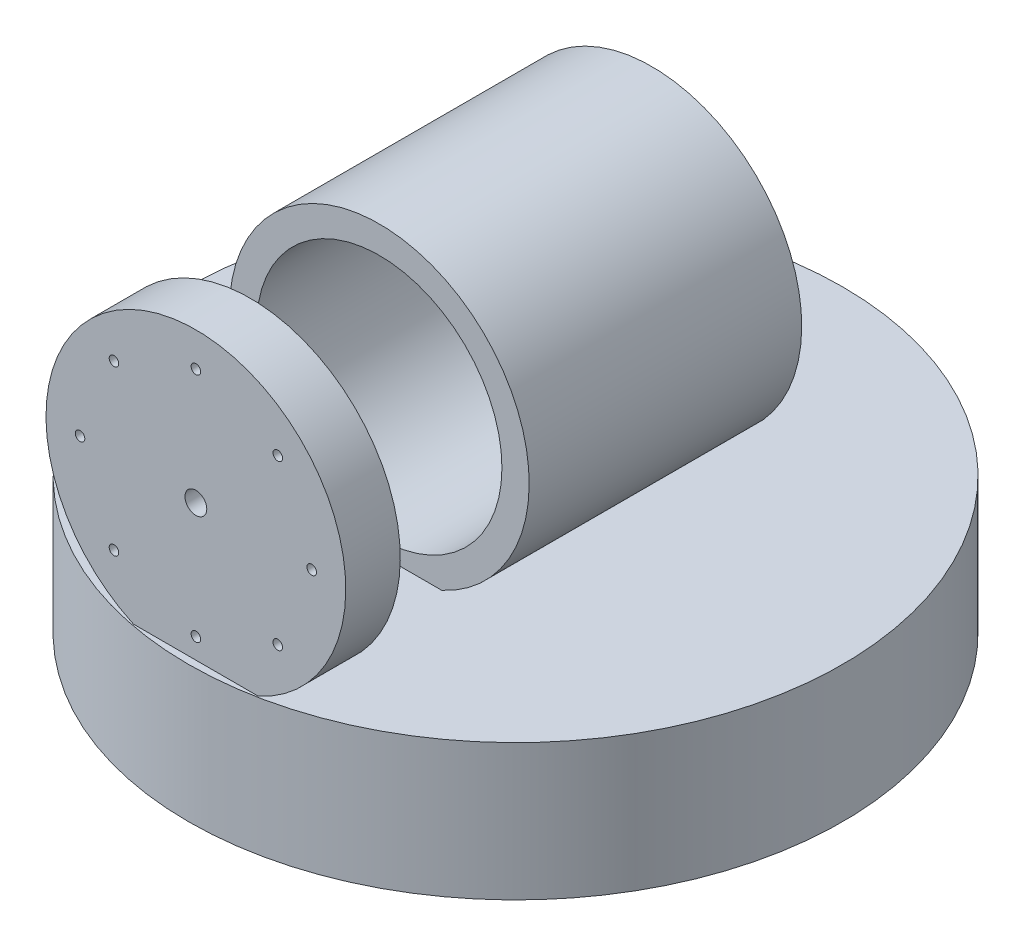
SolidWorks part; units mm, degrees
ref_plane "前视基准面" through (0, 0, 0) normal (0, 0, 1) x (1, 0, 0)
ref_plane "上视基准面" through (0, 0, 0) normal (0, 1, 0) x (1, 0, 0)
ref_plane "右视基准面" through (0, 0, 0) normal (1, 0, 0) x (0, 0, -1)
other "Configuration Table"
sketch "草图1" plane through (0, 0, 0) normal (0, 1, 0) x (1, 0, 0)
  circle A0 centre (0, 0) radius 120
extrude "凸台-拉伸1" add sketch "草图1" along normal blind 50
sketch "草图2" plane through (0, 0, 0) normal (0, 0, 1) x (1, 0, 0)
  line L0 (0, 50) -> (0, 100) construction
  line L1 (120, 50) -> (-120, 50) construction
  circle A0 centre (0, 100) radius 50
extrude "拉伸-薄壁1" add sketch "草图2" along normal blind 50 and the other way blind 50 thin thin type mid plane wall 10
sketch "草图3" plane through (0, 0, 50) normal (0, 0, 1) x (1, 0, 0)
  line L1 (-60, 152.3851) -> (120, 152.3851)
  line L2 (-60, 152.3851) -> (-60, 50)
  line L3 (-60, 50) -> (120, 50)
  line L4 (120, 152.3851) -> (120, 50)
  line L5 (-60, 152.3851) -> (120, 50) construction
  line L6 (-60, 50) -> (120, 152.3851) construction
  point P0 (30, 101.1925)
ref_plane "基准面1" through (0, 0, 55) normal (0, 0, 1) x (1, 0, 0)
sketch "草图4" plane through (0, 0, 55) normal (0, 0, 1) x (1, 0, 0)
  line L1 (-60, 152.3851) -> (120, 152.3851)
  line L2 (-60, 152.3851) -> (-60, 50)
  line L3 (-60, 50) -> (120, 50)
  line L4 (120, 152.3851) -> (120, 50)
  line L5 (-60, 152.3851) -> (120, 50) construction
  line L6 (-60, 50) -> (120, 152.3851) construction
  point P0 (30, 101.1925)
sketch "草图7" plane through (0, 0, 0) normal (0, -1, 0) x (1, 0, 0)
  circle A1 centre (17.25, 0) radius 2
  circle A2 centre (8.625, -14.9389) radius 2
  circle A3 centre (-8.625, -14.9389) radius 2
  circle A4 centre (-17.25, 0) radius 2
  circle A5 centre (-8.625, 14.9389) radius 2
  circle A6 centre (8.625, 14.9389) radius 2
  point P17 (0, 0)
  dimension "D2" = 4
  dimension "D3" = 6
extrude "切除-拉伸2" cut sketch "草图7" against normal blind 3
ref_plane "基准面2" through (0, 0, 97.3) normal (0, 0, 1) x (1, 0, 0)
sketch "草图8" plane through (0, 0, 97.3) normal (0, 0, 1) x (1, 0, 0)
  circle A0 centre (0, 100) radius 55
extrude "凸台-拉伸2" add sketch "草图8" along normal blind 20
sketch "草图9" plane through (0, 0, 97.3) normal (0, 0, -1) x (-1, 0, 0)
  circle A1 centre (42.5, 100) radius 1.75
  circle A2 centre (30.052, 69.948) radius 1.75
  circle A3 centre (0, 57.5) radius 1.75
  circle A4 centre (-30.052, 69.948) radius 1.75
  circle A5 centre (-42.5, 100) radius 1.75
  circle A6 centre (-30.052, 130.052) radius 1.75
  circle A7 centre (0, 142.5) radius 1.75
  circle A8 centre (30.052, 130.052) radius 1.75
  circle A9 centre (0, 100) radius 4
  point P21 (0, 100)
  dimension "D1" = 8
  dimension "D2" = 3.5
  dimension "D3" = 8
extrude "切除-拉伸3" cut sketch "草图9" against normal through all
